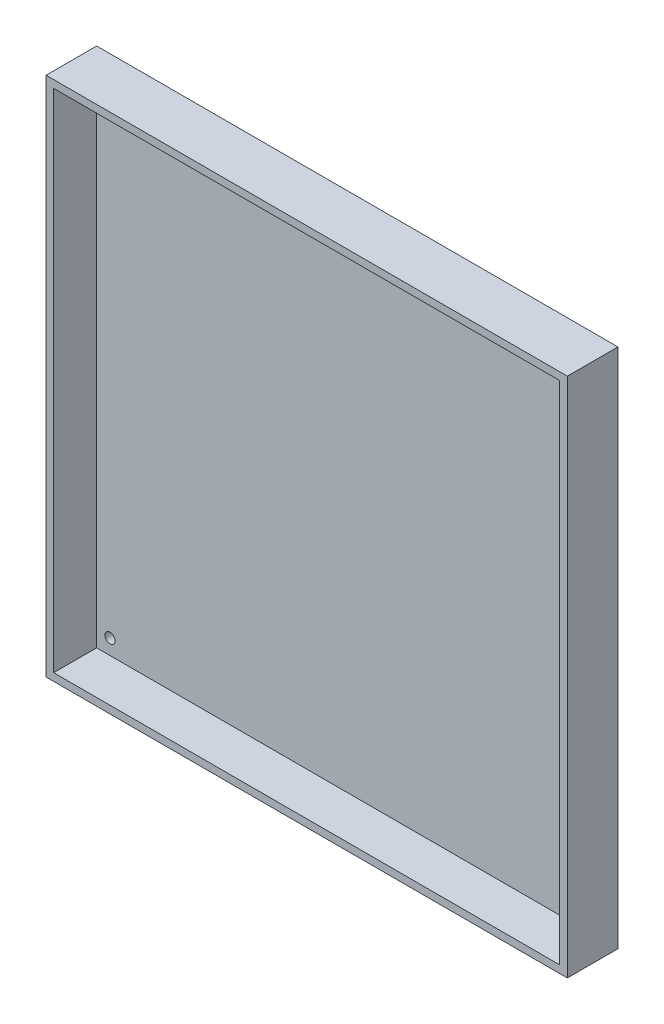
SolidWorks part; units mm, degrees
ref_plane "前视基准面" through (0, 0, 0) normal (0, 0, 1) x (1, 0, 0)
ref_plane "上视基准面" through (0, 0, 0) normal (0, 1, 0) x (1, 0, 0)
ref_plane "右视基准面" through (0, 0, 0) normal (1, 0, 0) x (0, 0, -1)
sketch "草图1" plane through (0, 0, 0) normal (0, 0, 1) x (1, 0, 0)
  line L0 (0, 0) -> (103, 0)
  line L1 (103, 0) -> (103, -103)
  line L2 (103, -103) -> (0, -103)
  line L3 (0, -103) -> (0, 0)
extrude "凸台-拉伸1" add sketch "草图1" along normal blind 1.5
sketch "草图3" plane through (0, 0, 1.5) normal (0, 0, 1) x (1, 0, 0)
  line L2 (103, -103) -> (0, -103)
  line L3 (0, -103) -> (0, 0)
  line L4 (0, 0) -> (103, 0)
  line L5 (1.5, -1.5) -> (1.5, -101.5)
  line L6 (1.5, -101.5) -> (101.5, -101.5)
  line L7 (101.5, -101.5) -> (101.5, -1.5)
  line L8 (101.5, -1.5) -> (1.5, -1.5)
  line L10 (103, 0) -> (103, -103)
  line L11 (0, -103) -> (0, 0)
  line M6 (0, 0) -> (0, -103)
  line M7 (0, -103) -> (103, -103)
  line M8 (103, -103) -> (103, 0)
  line M9 (103, 0) -> (0, 0)
extrude "凸台-拉伸2" add sketch "草图3" along normal blind 8.5 contours L8 L7 L6 L5 M9 M6 M7 M8
sketch "草图4" plane through (0, 0, 1.5) normal (0, 0, 1) x (1, 0, 0)
  circle A0 centre (4.5, -4.5) radius 1
  circle A1 centre (98.5, -4.5) radius 1
  circle A2 centre (4.1264, -98.5) radius 1
  circle A3 centre (98.5, -98.5) radius 1
extrude "切除-拉伸1" cut sketch "草图4" against normal blind 1.5 contours A2 | A3 | A1 | A0
